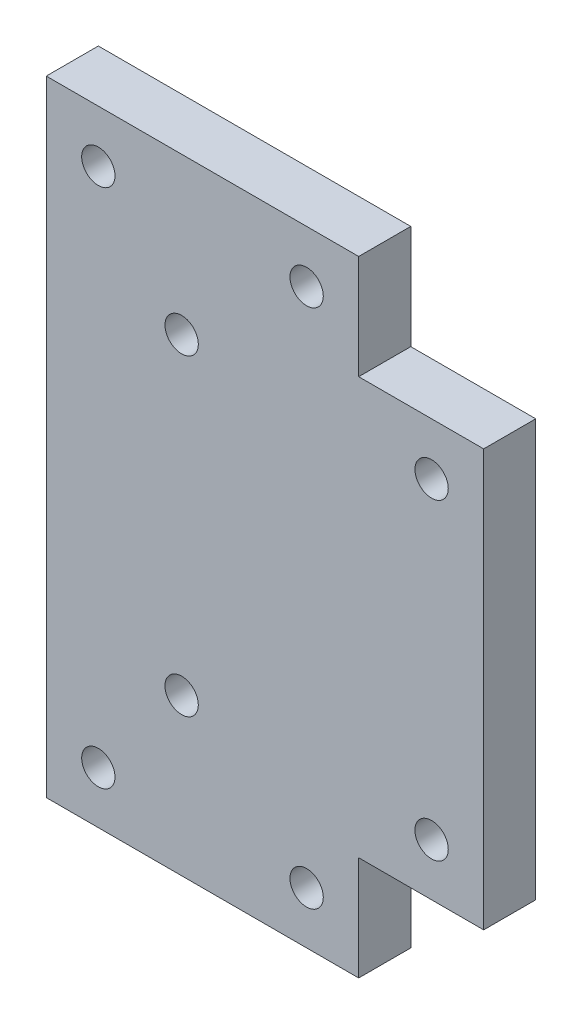
SolidWorks part; units mm, degrees
ref_plane "Front" through (0, 0, 0) normal (0, 0, 1) x (1, 0, 0)
ref_plane "Top" through (0, 0, 0) normal (0, 1, 0) x (1, 0, 0)
ref_plane "Right" through (0, 0, 0) normal (1, 0, 0) x (0, 0, -1)
sketch "四轮中心位置" plane through (0, 0, 0) normal (0, 0, 1) x (1, 0, 0)
  line L1 (0, 0) -> (180, 0)
  line L2 (0, 0) -> (0, 180)
  line L3 (0, 180) -> (180, 180)
  line L4 (180, 0) -> (180, 180)
  dimension "D1" = 180
  dimension "D2" = 180
sketch "四轮示意图" plane through (0, 0, 0) normal (0, 0, 1) x (1, 0, 0)
  line L1 (16, 137.5) -> (-16, 137.5)
  line L2 (16, 137.5) -> (16, 222.5)
  line L3 (16, 222.5) -> (-16, 222.5)
  line L4 (-16, 137.5) -> (-16, 222.5)
  line L5 (16, 137.5) -> (-16, 222.5) construction
  line L6 (16, 222.5) -> (-16, 137.5) construction
  line L7 (196, 137.5) -> (164, 137.5)
  line L8 (196, 137.5) -> (196, 222.5)
  line L9 (196, 222.5) -> (164, 222.5)
  line L10 (164, 137.5) -> (164, 222.5)
  line L11 (196, 137.5) -> (164, 222.5) construction
  line L12 (196, 222.5) -> (164, 137.5) construction
  line L13 (-16, -42.5) -> (16, -42.5)
  line L14 (-16, -42.5) -> (-16, 42.5)
  line L15 (-16, 42.5) -> (16, 42.5)
  line L16 (16, -42.5) -> (16, 42.5)
  line L17 (-16, -42.5) -> (16, 42.5) construction
  line L18 (-16, 42.5) -> (16, -42.5) construction
  line L19 (164, -42.5) -> (196, -42.5)
  line L20 (164, -42.5) -> (164, 42.5)
  line L21 (164, 42.5) -> (196, 42.5)
  line L22 (196, -42.5) -> (196, 42.5)
  line L23 (164, -42.5) -> (196, 42.5) construction
  line L24 (164, 42.5) -> (196, -42.5) construction
  point P0 (0, 180)
  point P5 (180, 180)
  point P11 (0, 0)
  point P17 (180, 0)
  dimension "D1" = 32
  dimension "D2" = 85
  dimension "D3" = 32
  dimension "D4" = 85
  dimension "D5" = 32
  dimension "D6" = 85
  dimension "D7" = 32
  dimension "D8" = 85
sketch "草图3" plane through (0, 0, 0) normal (0, 0, 1) x (1, 0, 0)
  line L0 (-10, 267.5) -> (190, 267.5)
  line L1 (190, 267.5) -> (190, 230)
  line L2 (190, 230) -> (160, 230)
  line L3 (160, 230) -> (160, 130)
  line L4 (160, 130) -> (190, 130)
  line L5 (190, 130) -> (190, 50)
  line L6 (190, 50) -> (160, 50)
  line L7 (160, 50) -> (160, -50)
  line L8 (160, -50) -> (190, -50)
  line L9 (190, -50) -> (190, -87.5)
  line L10 (190, -87.5) -> (-10, -87.5)
  line L11 (-10, -87.5) -> (-10, -50)
  line L12 (-10, -50) -> (20, -50)
  line L13 (20, -50) -> (20, 50)
  line L14 (20, 50) -> (-10, 50)
  line L15 (-10, 50) -> (-10, 130)
  line L16 (-10, 130) -> (20, 130)
  line L17 (20, 130) -> (20, 230)
  line L18 (20, 230) -> (-10, 230)
  line L19 (-10, 230) -> (-10, 267.5)
  line L20 (0, 0) -> (180, 0) construction
  line L21 (0, 0) -> (0, 180) construction
  point P22 (90, -87.5)
  point P23 (90, 0)
  point P24 (-10, 90)
  point P27 (0, 90)
  dimension "D1" = 200
  dimension "D2" = 355
  dimension "D3" = 100
  dimension "D4" = 100
  dimension "D5" = 100
  dimension "D6" = 100
  dimension "D7" = 30
  dimension "D8" = 30
  dimension "D9" = 30
  dimension "D10" = 30
  dimension "D11" = 80
  dimension "D12" = 37.5
  dimension "D13" = 80
  dimension "D14" = 37.5
  dimension "D15" = 30
  dimension "D16" = 30
  dimension "D17" = 0
  dimension "D18" = 0
  dimension "D19" = 200
  dimension "D20" = 0
extrude "凸台-拉伸1" add sketch "草图3" along normal blind 5
sketch "草图4" plane through (0, 0, 5) normal (0, 0, 1) x (1, 0, 0)
  line L1 (33, 195) -> (57, 195)
  line L2 (33, 195) -> (33, 165)
  line L3 (33, 165) -> (57, 165)
  line L4 (57, 195) -> (57, 165)
  line L5 (33, 15) -> (57, 15)
  line L6 (33, 15) -> (33, -15)
  line L7 (33, -15) -> (57, -15)
  line L8 (57, 15) -> (57, -15)
  line L9 (123, 195) -> (147, 195)
  line L10 (123, 195) -> (123, 165)
  line L11 (123, 165) -> (147, 165)
  line L12 (147, 195) -> (147, 165)
  line L13 (123, 15) -> (147, 15)
  line L14 (123, 15) -> (123, -15)
  line L15 (123, -15) -> (147, -15)
  line L16 (147, 15) -> (147, -15)
  point P20 (57, 195)
  point P22 (33, 165)
  point P23 (57, 165)
  dimension "D1" = 24
  dimension "D2" = 30
  dimension "D3" = 33
  dimension "D4" = 15
  dimension "D5" = 24
  dimension "D6" = 30
  dimension "D7" = 33
  dimension "D8" = 15
  dimension "D9" = 24
  dimension "D10" = 30
  dimension "D11" = 33
  dimension "D12" = 15
  dimension "D13" = 24
  dimension "D14" = 30
  dimension "D15" = 15
  dimension "D16" = 33
sketch "草图5" plane through (0, 0, 5) normal (0, 0, 1) x (1, 0, 0)
  circle A0 centre (33, 195) radius 1.6
  circle A1 centre (57, 195) radius 1.6
  circle A2 centre (33, 165) radius 1.6
  circle A3 centre (57, 165) radius 1.6
  circle A4 centre (123, 195) radius 1.6
  circle A5 centre (147, 195) radius 1.6
  circle A6 centre (123, 165) radius 1.6
  circle A7 centre (147, 165) radius 1.6
  circle A8 centre (33, 15) radius 1.6
  circle A9 centre (57, 15) radius 1.6
  circle A10 centre (33, -15) radius 1.6
  circle A11 centre (57, -15) radius 1.6
  circle A12 centre (123, 15) radius 1.6
  circle A13 centre (147, 15) radius 1.6
  circle A14 centre (123, -15) radius 1.6
  circle A15 centre (147, -15) radius 1.6
  dimension "D1" = 3.2
  dimension "D2" = 3.2
extrude "切除-拉伸1" cut sketch "草图5" against normal through all
sketch "草图6" plane through (0, 0, 5) normal (0, 0, 1) x (1, 0, 0)
  line L0 (-10, 130) -> (-10, 50) construction
  line L1 (-10, 105) -> (-7, 105)
  line L2 (-10, 105) -> (-10, 75)
  line L3 (-10, 75) -> (-7, 75)
  line L4 (-7, 105) -> (-7, 75)
  line L5 (190, 50) -> (190, 130) construction
  line L7 (187, 105) -> (190, 105)
  line L8 (187, 105) -> (187, 75)
  line L9 (187, 75) -> (190, 75)
  line L10 (190, 105) -> (190, 75)
  point P6 (-7, 90)
  point P9 (190, 90)
  point P14 (190, 90)
  dimension "D1" = 30
  dimension "D2" = 3
  dimension "D3" = 0
  dimension "D4" = 3
  dimension "D5" = 30
  dimension "D6" = 0
  dimension "D7" = 0
extrude "切除-拉伸2" cut sketch "草图6" against normal through all
sketch "草图7" plane through (0, 0, 5) normal (0, 0, 1) x (1, 0, 0)
  line L0 (-10, 267.5) -> (-10, 230) construction
  line L1 (-10, 253.75) -> (-7, 253.75)
  line L2 (-10, 253.75) -> (-10, 243.75)
  line L3 (-10, 243.75) -> (-7, 243.75)
  line L4 (-7, 253.75) -> (-7, 243.75)
  line L5 (190, 230) -> (190, 267.5) construction
  line L6 (187, 253.75) -> (190, 253.75)
  line L7 (187, 253.75) -> (187, 243.75)
  line L8 (187, 243.75) -> (190, 243.75)
  line L9 (190, 253.75) -> (190, 243.75)
  line L10 (-10, -50) -> (-10, -87.5) construction
  line L11 (-10, -63.75) -> (-7, -63.75)
  line L12 (-10, -63.75) -> (-10, -73.75)
  line L13 (-10, -73.75) -> (-7, -73.75)
  line L14 (-7, -63.75) -> (-7, -73.75)
  line L15 (190, -87.5) -> (190, -50) construction
  line L16 (187, -63.75) -> (190, -63.75)
  line L17 (187, -63.75) -> (187, -73.75)
  line L18 (187, -73.75) -> (190, -73.75)
  line L19 (190, -63.75) -> (190, -73.75)
  point P4 (-10, 248.75)
  point P7 (-10, 248.75)
  point P12 (190, 248.75)
  point P15 (190, 248.75)
  point P20 (-10, -68.75)
  point P23 (-10, -68.75)
  point P28 (190, -68.75)
  point P31 (190, -68.75)
  dimension "D1" = 3
  dimension "D2" = 10
  dimension "D3" = 0
  dimension "D4" = 0
  dimension "D5" = 3
  dimension "D6" = 10
  dimension "D7" = 0
  dimension "D8" = 0
  dimension "D9" = 3
  dimension "D10" = 10
  dimension "D11" = 0
  dimension "D12" = 0
  dimension "D13" = 3
  dimension "D14" = 10
  dimension "D15" = 0
  dimension "D16" = 0
extrude "切除-拉伸3" cut sketch "草图7" against normal through all
sketch "草图8" plane through (0, 0, 5) normal (0, 0, 1) x (1, 0, 0)
  line L0 (-10, -87.5) -> (190, -87.5) construction
  line L1 (10, -87.5) -> (25, -87.5)
  line L2 (10, -87.5) -> (10, -84.5)
  line L3 (10, -84.5) -> (25, -84.5)
  line L4 (25, -87.5) -> (25, -84.5)
  line L6 (45, -87.5) -> (60, -87.5)
  line L7 (45, -87.5) -> (45, -84.5)
  line L8 (45, -84.5) -> (60, -84.5)
  line L9 (60, -87.5) -> (60, -84.5)
  line L10 (120, -87.5) -> (135, -87.5)
  line L11 (120, -87.5) -> (120, -84.5)
  line L12 (120, -84.5) -> (135, -84.5)
  line L13 (135, -87.5) -> (135, -84.5)
  line L14 (155, -87.5) -> (170, -87.5)
  line L15 (155, -87.5) -> (155, -84.5)
  line L16 (155, -84.5) -> (170, -84.5)
  line L17 (170, -87.5) -> (170, -84.5)
  point P10 (90, -87.5)
  dimension "D1" = 15
  dimension "D2" = 3
  dimension "D3" = 15
  dimension "D4" = 3
  dimension "D5" = 20
  dimension "D6" = 30
  dimension "D7" = 15
  dimension "D8" = 30
  dimension "D9" = 20
  dimension "D10" = 15
extrude "切除-拉伸4" cut sketch "草图8" against normal through all
sketch "草图9" plane through (0, 0, 5) normal (0, 0, 1) x (1, 0, 0)
  line L0 (20, 230) -> (20, 130) construction
  line L1 (-10, 230) -> (20, 230)
  line L2 (-10, 230) -> (-10, 229.64)
  line L3 (-10, 229.64) -> (20, 229.64)
  line L4 (20, 230) -> (20, 229.64)
  line L6 (160, 230) -> (190, 230)
  line L7 (160, 230) -> (160, 229.64)
  line L8 (160, 229.64) -> (190, 229.64)
  line L9 (190, 230) -> (190, 229.64)
  dimension "D1" = 0.36
  dimension "D2" = 0.36
extrude "凸台-拉伸2" add sketch "草图9" against normal blind 5
sketch "草图10" plane through (0, 0, 5) normal (0, 0, 1) x (1, 0, 0)
  line L1 (66, 200) -> (26, 200)
  line L2 (66, 200) -> (66, 160)
  line L3 (66, 160) -> (26, 160)
  line L4 (26, 200) -> (26, 160)
  circle A1 centre (33, 195) radius 1.6 construction
  dimension "D3" = 5
  dimension "D1" = 40
  dimension "D2" = 40
  dimension "D4" = 7
sketch "草图11" plane through (0, 0, 5) normal (0, 0, 1) x (1, 0, 0)
  line L0 (20, 229.64) -> (20, 130) construction
  line L1 (20, 210) -> (66, 210)
  line L2 (20, 210) -> (20, 150)
  line L3 (20, 150) -> (66, 150)
  line L4 (66, 210) -> (66, 150)
  line L5 (66, 200) -> (26, 200) construction
  line L6 (66, 160) -> (26, 160) construction
  line L7 (66, 200) -> (66, 160) construction
  line L9 (190, 267.5) -> (-10, 267.5)
  line L10 (190, 267.5) -> (190, -87.5)
  line L11 (190, -87.5) -> (-10, -87.5)
  line L12 (-10, 267.5) -> (-10, -87.5)
  dimension "D1" = 10
  dimension "D2" = 10
  dimension "D3" = 0
extrude "切除-拉伸5" cut sketch "草图11" against normal through all
sketch "草图13" plane through (0, 0, 5) normal (0, 0, 1) x (1, 0, 0)
  line L0 (66, 210) -> (20, 210) construction
  line L2 (20, 210) -> (20, 150) construction
  line L3 (20, 150) -> (66, 150) construction
  line L4 (20, 210) -> (20, 150) construction
  circle A0 centre (45, 205) radius 1.6
  circle A1 centre (25, 155) radius 1.6
  circle A2 centre (25, 205) radius 1.6
  circle A3 centre (45, 155) radius 1.6
  dimension "D1" = 5
  dimension "D2" = 20
  dimension "D3" = 5
  dimension "D4" = 5
  dimension "D5" = 20
  dimension "D6" = 5
sketch "草图14" plane through (0, 0, 0) normal (0, 0, -1) x (-1, 0, 0)
  line L1 (-66, 150) -> (-50, 150)
  line L2 (-66, 150) -> (-66, 160)
  line L3 (-62, 160) -> (-50, 160)
  line L4 (-50, 150) -> (-50, 160)
  line L5 (-66, 210) -> (-50, 210)
  line L6 (-66, 210) -> (-66, 200)
  line L7 (-62, 200) -> (-50, 200)
  line L8 (-50, 210) -> (-50, 200)
  line L10 (-66, 160) -> (-66, 200)
  line L12 (-62, 160) -> (-62, 200)
  circle A0 centre (-57, 165) radius 1.6 construction
  circle A1 centre (-57, 195) radius 1.6 construction
  dimension "D1" = 7
  dimension "D2" = 10
  dimension "D3" = 10
  dimension "D4" = 5
  dimension "D5" = 7
extrude "切除-拉伸7" cut sketch "草图14" against normal through all
extrude "切除-拉伸8" cut sketch "草图13" against normal through all
